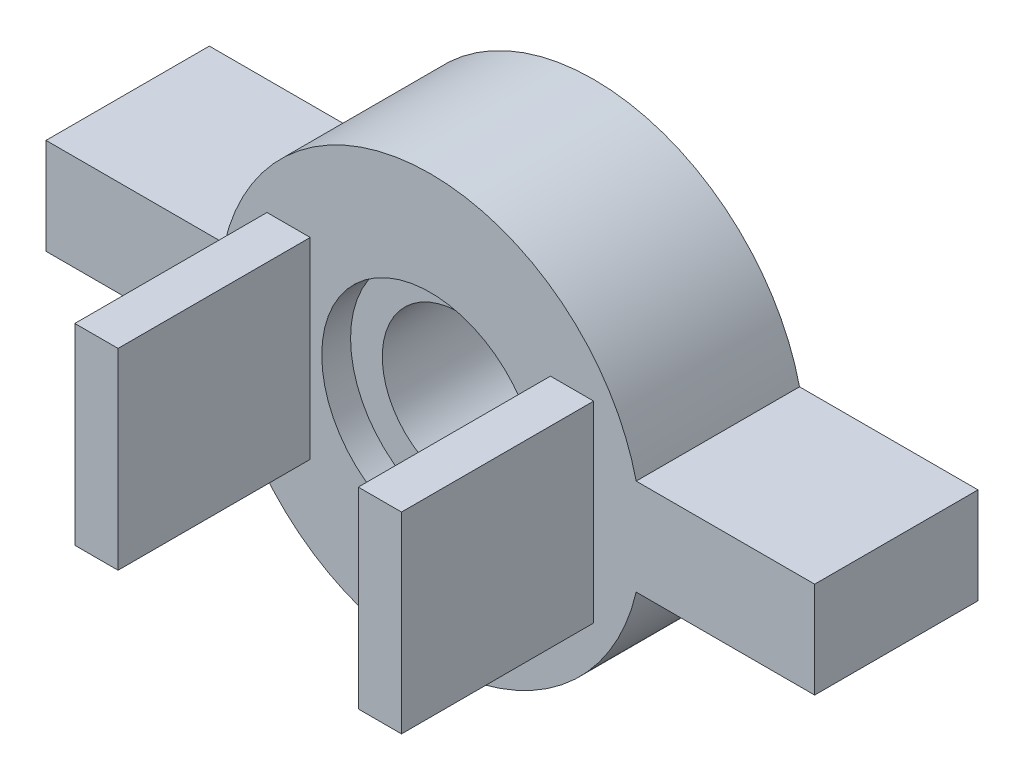
SolidWorks part; units mm, degrees
ref_plane "Front Plane" through (0, 0, 0) normal (0, 0, 1) x (1, 0, 0)
ref_plane "Top Plane" through (0, 0, 0) normal (0, 1, 0) x (1, 0, 0)
ref_plane "Right Plane" through (0, 0, 0) normal (1, 0, 0) x (0, 0, -1)
sketch "Sketch1" plane through (0, 0, 0) normal (0, 0, 1) x (1, 0, 0)
  line L0 (10.7121, 2.5) -> (20, 2.5)
  line L1 (-20, 2.5) -> (-10.7121, 2.5)
  line L2 (-20, 2.5) -> (-20, -2.5)
  line L3 (-20, -2.5) -> (-10.7121, -2.5)
  line L4 (20, 2.5) -> (20, -2.5)
  line L5 (-20, 2.5) -> (20, -2.5) construction
  line L6 (-20, -2.5) -> (20, 2.5) construction
  line L7 (10.7121, -2.5) -> (20, -2.5)
  arc A0 (-10.7121, -2.5) -> (10.7121, -2.5) centre (0, 0) ccw
  arc A1 (10.7121, 2.5) -> (-10.7121, 2.5) centre (0, 0) ccw
  dimension "D1" = 22
  dimension "D2" = 5
  dimension "D3" = 40
extrude "Boss-Extrude1" add sketch "Sketch1" along normal blind 8.5
sketch "Sketch2" plane through (0, 0, 8.5) normal (0, 0, 1) x (1, 0, 0)
  circle A0 centre (0, 0) radius 4
  dimension "D1" = 8
extrude "Cut-Extrude1" cut sketch "Sketch2" against normal up to next
sketch "Sketch3" plane through (0, 0, 8.5) normal (0, 0, 1) x (1, 0, 0)
  line L0 (6.25, 5) -> (8.5, 5)
  line L2 (-6.25, -5) -> (-6.25, 5)
  line L3 (6.25, -5) -> (8.5, -5)
  line L4 (6.25, -5) -> (6.25, 5)
  line L5 (-6.25, -5) -> (6.25, 5) construction
  line L6 (-6.25, 5) -> (6.25, -5) construction
  line L7 (-8.5, 5) -> (-6.25, 5)
  line L8 (-8.5, 5) -> (-8.5, -5)
  line L9 (-8.5, -5) -> (-6.25, -5)
  line L10 (8.5, 5) -> (8.5, -5)
  line L11 (-8.5, 5) -> (8.5, -5) construction
  line L12 (-8.5, -5) -> (8.5, 5) construction
  point P0 (0, 0)
  point P6 (0, 0)
  point P11 (-10.747, 5)
  point P12 (0, 0)
  dimension "D1" = 12.5
  dimension "D2" = 10
  dimension "D3" = 17
extrude "Boss-Extrude3" add sketch "Sketch3" along normal blind 10
sketch "Sketch4" plane through (0, 0, 8.5) normal (0, 0, 1) x (1, 0, 0)
  circle A0 centre (0, 0) radius 5.65
  dimension "D1" = 11.3
extrude "Cut-Extrude2" cut sketch "Sketch4" against normal blind 1.5
